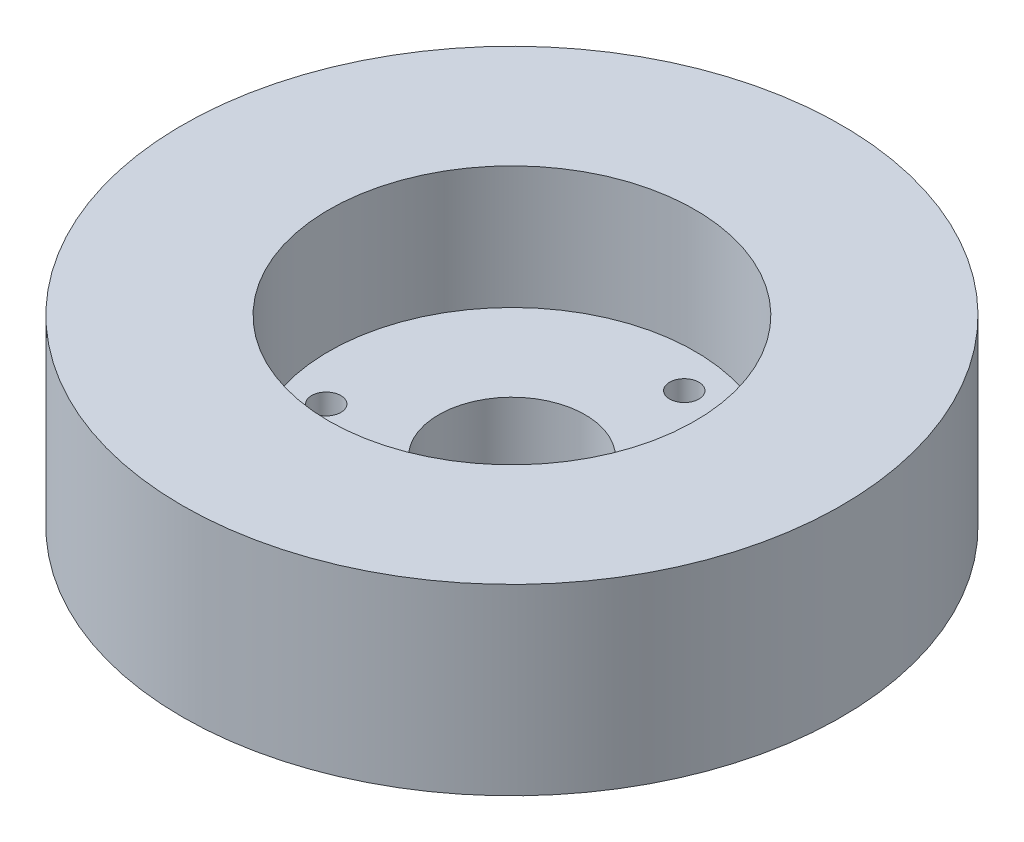
SolidWorks part; units mm, degrees
ref_plane "Front Plane" through (0, 0, 0) normal (0, 0, 1) x (1, 0, 0)
ref_plane "Top Plane" through (0, 0, 0) normal (0, 1, 0) x (1, 0, 0)
ref_plane "Right Plane" through (0, 0, 0) normal (1, 0, 0) x (0, 0, -1)
sketch "Sketch1" plane through (0, 0, 0) normal (0, 1, 0) x (1, 0, 0)
  circle A0 centre (0, 0) radius 90
  dimension "D1" = 180
extrude "Boss-Extrude1" add sketch "Sketch1" along normal blind 50
sketch "Sketch2" plane through (0, 50, 0) normal (0, 1, 0) x (1, 0, 0)
  circle A0 centre (0, 0) radius 50
  dimension "D1" = 100
extrude "Cut-Extrude1" cut sketch "Sketch2" against normal blind 33.5
sketch "Sketch3" plane through (0, 16.5, 0) normal (0, 1, 0) x (1, 0, 0)
  circle A0 centre (0, 0) radius 20
  dimension "D1" = 40
extrude "Cut-Extrude2" cut sketch "Sketch3" against normal blind 35
sketch "Sketch4" plane through (0, 0, 0) normal (0, -1, 0) x (1, 0, 0)
  circle A0 centre (-37.8892, 12.8223) radius 4
  circle A1 centre (7.8402, -39.2241) radius 4
  circle A2 centre (30.049, 26.4019) radius 4
extrude "Cut-Extrude3" cut sketch "Sketch4" against normal blind 72
